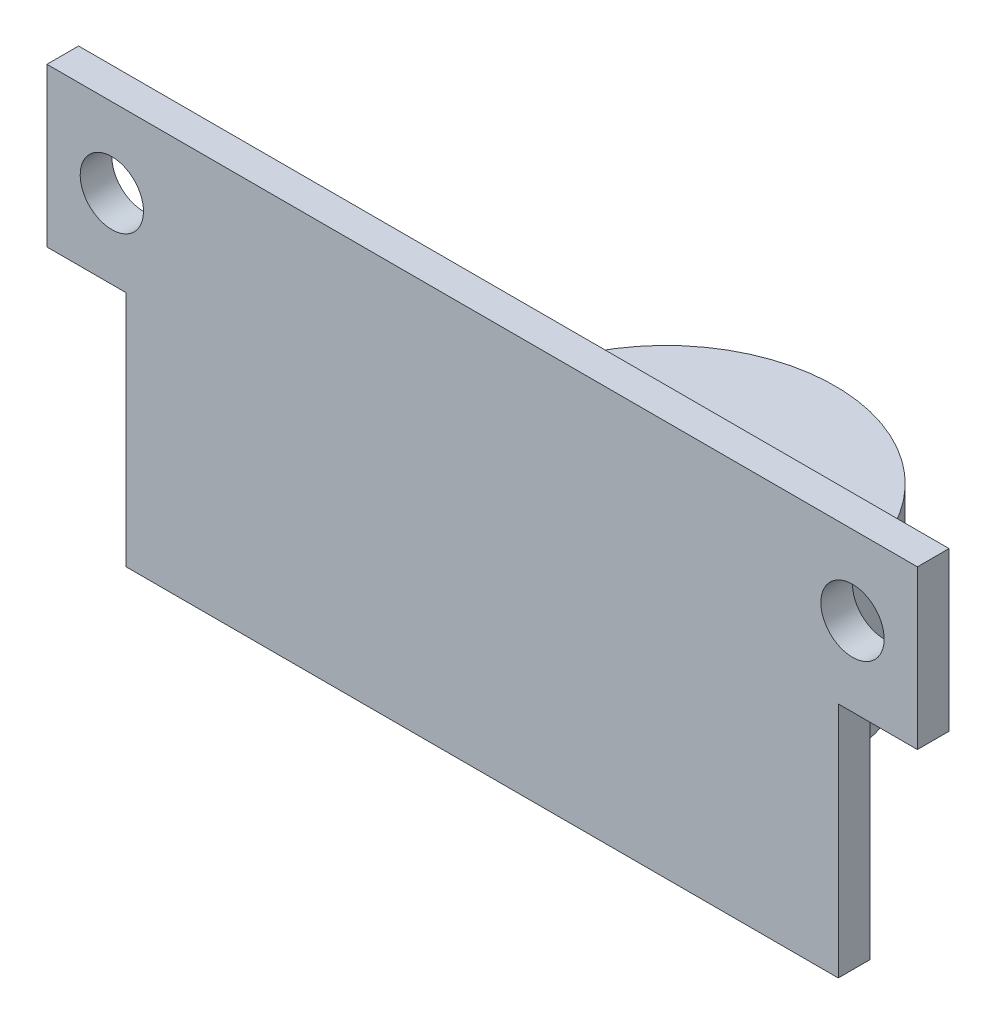
SolidWorks part; units mm, degrees
ref_plane "Front Plane" through (0, 0, 0) normal (0, 0, 1) x (1, 0, 0)
ref_plane "Top Plane" through (0, 0, 0) normal (0, 1, 0) x (1, 0, 0)
ref_plane "Right Plane" through (0, 0, 0) normal (1, 0, 0) x (0, 0, -1)
sketch "Sketch1" plane through (0, 0, 0) normal (0, 0, 1) x (1, 0, 0)
  line L0 (42.5066, -10) -> (-12.4934, -10)
  line L1 (42.5066, -10) -> (42.5066, 0)
  line L2 (-12.4934, -10) -> (-12.4934, 0)
  line L3 (42.5066, 0) -> (-12.4934, 0)
  line L4 (42.5066, -10) -> (42.5066, 0) construction
  line L5 (-12.4934, -10) -> (42.5066, -10) construction
  line L6 (42.5066, 0) -> (-12.4934, 0) construction
  line L7 (37.5066, -10) -> (-7.4934, -10)
  line L8 (37.5066, -10) -> (37.5066, -25)
  line L9 (-7.4934, -10) -> (-7.4934, -25)
  line L10 (37.5066, -25) -> (-7.4934, -25)
  line L11 (37.5066, -25) -> (-7.4934, -25) construction
  line L12 (37.5066, -80.75) -> (37.5066, -25) construction
  line L13 (-7.4934, -80.75) -> (-7.4934, -25) construction
  circle A0 centre (38.4066, -5) radius 2
  circle A1 centre (-8.3934, -5) radius 2
extrude "Boss-Extrude1" add sketch "Sketch1" against normal blind 2 from surface contours L10 L8 L0 L9 | L1 L3 L2 L0 A1 A0
sketch "Sketch2" plane through (0, -25, 0) normal (0, 1, 0) x (1, 0, 0)
  circle A0 centre (15.0066, 5.6) radius 10.7
  circle A1 centre (15.0066, 5.6) radius 4.1
  dimension "D1" = 8.2
extrude "Boss-Extrude2" add sketch "Sketch2" along normal blind 10
sketch "Sketch3" plane through (0, -15, 0) normal (0, 1, 0) x (1, 0, 0)
  line L0 (4.3066, 5.6) -> (25.7066, 5.6)
  line L1 (4.3066, 5.6) -> (4.3066, -6)
  line L2 (25.7066, 5.6) -> (25.7066, -6)
  line L3 (4.3066, -6) -> (25.7066, -6)
  line L4 (42.5066, -6) -> (-12.4934, -6) construction
  arc A0 (19.732, -4) -> (10.2811, -4) centre (15.0066, 5.6) ccw construction
  circle A1 centre (15.0066, 5.6) radius 4.1
  circle A2 centre (15.0066, 5.6) radius 4.1 construction
  arc M1 (19.732, -4) -> (10.2811, -4) centre (15.0066, 5.6) ccw
  line M2 (10.2811, -4) -> (19.732, -4)
  circle M3 centre (15.0066, 5.6) radius 4.1
extrude "Boss-Extrude3" add sketch "Sketch3" against normal blind 10 contours L0 M1 M2 M3 | L1 L3 L2 M1 M2
